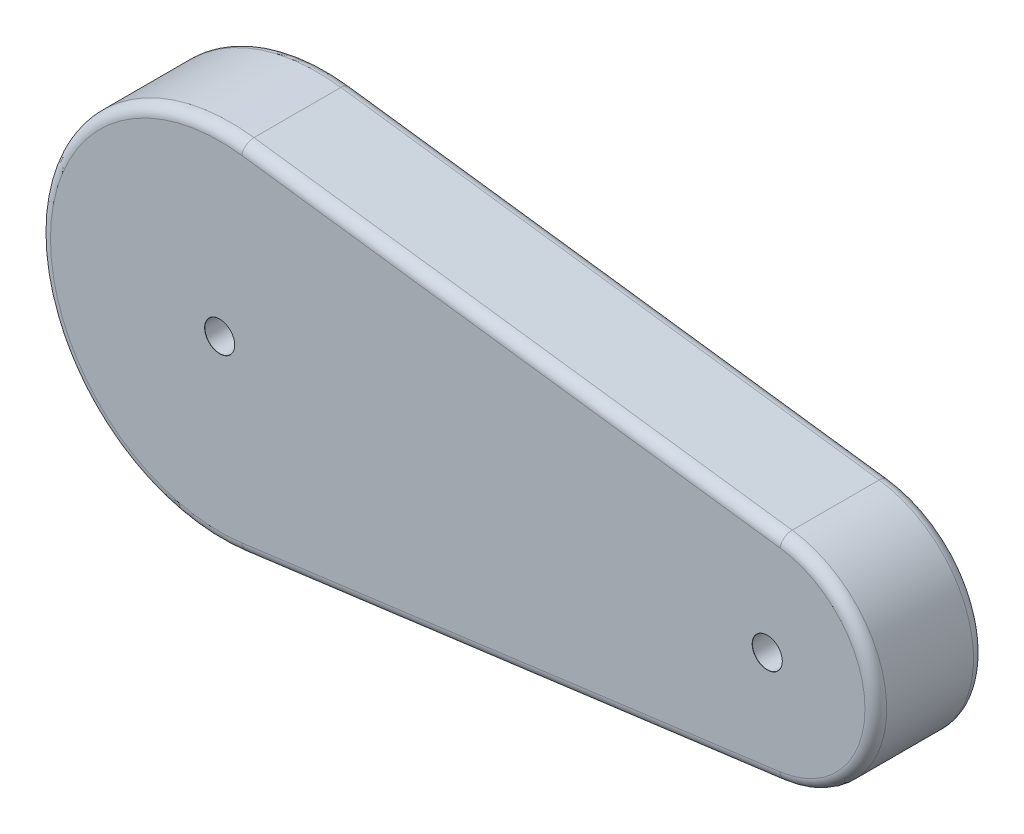
SolidWorks part; units mm, degrees
ref_plane "Plan de face" through (0, 0, 0) normal (0, 0, 1) x (1, 0, 0)
ref_plane "Plan de dessus" through (0, 0, 0) normal (0, 1, 0) x (1, 0, 0)
ref_plane "Plan de droite" through (0, 0, 0) normal (1, 0, 0) x (0, 0, -1)
sketch "Profil Bras" plane through (0, 0, 0) normal (0, 0, 1) x (1, 0, 0)
  line L2 (-46.1025, 32.8815) -> (53.042, 19.8289)
  line L3 (53.042, -19.8289) -> (-46.1025, -32.8815)
  line L4 (-50.4314, 0) -> (50.4314, 0) construction
  arc A2 (53.042, 19.8289) -> (53.042, -19.8289) centre (50.4314, 0) cw
  arc A3 (-46.1025, -32.8815) -> (-46.1025, 32.8815) centre (-50.4314, 0) cw
  point P5 (0, 0)
  point P8 (0, 0)
  dimension "D1" = 20
  dimension "D2" = 15
  dimension "D3" = 100
extrude "Bras" add sketch "Profil Bras" along normal mid plane 20
hole_wizard "Perçage M51" positions "Esquisse2" profile "Esquisse3" hole size "M5" standard "Ansi Metric" end condition through all
sketch "Esquisse2" plane through (0, 0, 10) normal (0, 0, 1) x (1, 0, 0)
  point P0 (-50.4314, 0)
  point P3 (50.4314, 0)
sketch "Esquisse3" plane through (-50.4314, 0, 10) normal (1, 0, 0) x (0, -1, 0)
  line L0 (0, 0) -> (0, 20)
  line L1 (0, 20) -> (2.75, 20)
  line L2 (2.75, 20) -> (2.75, 0.025)
  line L3 (2.75, 0.025) -> (2.775, 0)
  line L5 (2.775, 0) -> (0, 0)
  line L6 (-2.75, 0.025) -> (-2.775, 0) construction
  line L11 (0, -6.35) -> (0, 107.95) construction
  dimension "Diamètre du perçage jusqu'au prochain" = 5.5
  dimension "Profondeur du perçage jusqu'au prochain" = 20
  dimension "Diamètre du fraisage entrant" = 5.55
  dimension "Angle du fraisage entrant" = 90
fillet "Congé1" radius 2 8 edges at (70.4314, 0, -10) (3.4697, -26.3552, -10) (-83.5967, 0, -10) (70.4314, 0, 10) (3.4697, -26.3552, 10) (-83.5967, 0, 10) (3.4697, 26.3552, -10) (3.4697, 26.3552, 10)
